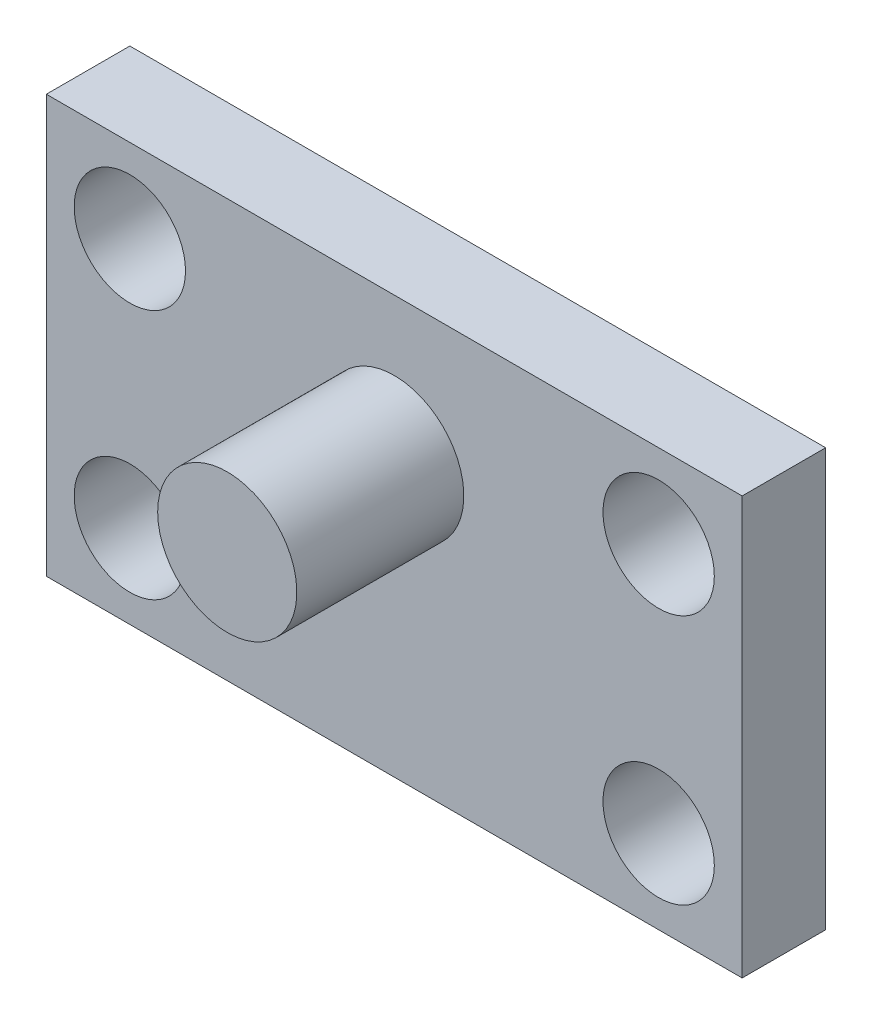
SolidWorks part; units mm, degrees
ref_plane "Front Plane" through (0, 0, 0) normal (0, 0, 1) x (1, 0, 0)
ref_plane "Top Plane" through (0, 0, 0) normal (0, 1, 0) x (1, 0, 0)
ref_plane "Right Plane" through (0, 0, 0) normal (1, 0, 0) x (0, 0, -1)
sketch "Sketch1" plane through (0, 0, 0) normal (0, 0, 1) x (1, 0, 0)
  line L1 (0, 0) -> (250, 0)
  line L2 (0, 0) -> (0, 150)
  line L3 (0, 150) -> (250, 150)
  line L4 (250, 0) -> (250, 150)
  circle A0 centre (30, 30) radius 20
  circle A1 centre (220, 30) radius 20
  circle A2 centre (220, 120) radius 20
  circle A3 centre (30, 120) radius 20
  dimension "D3" = 40
  dimension "D1" = 250
  dimension "D2" = 150
  dimension "D4" = 30
  dimension "D5" = 30
  dimension "D6" = 2
  dimension "D7" = 2
extrude "Boss-Extrude1" add sketch "Sketch1" along normal blind 30
sketch "Sketch2" plane through (0, 0, 0) normal (0, 0, 1) x (1, 0, 0)
  line L0 (0, 150) -> (0, 0) construction
  line L2 (250, 150) -> (0, 150) construction
  circle A0 centre (125, 100) radius 25
  point P6 (136.0266, 150)
  point P7 (0, 0)
  point P8 (0, 0)
  point P9 (0, 0)
  dimension "D3" = 50
  dimension "D1" = 125
  dimension "D2" = 50
extrude "Boss-Extrude3" add sketch "Sketch2" along normal blind 90
